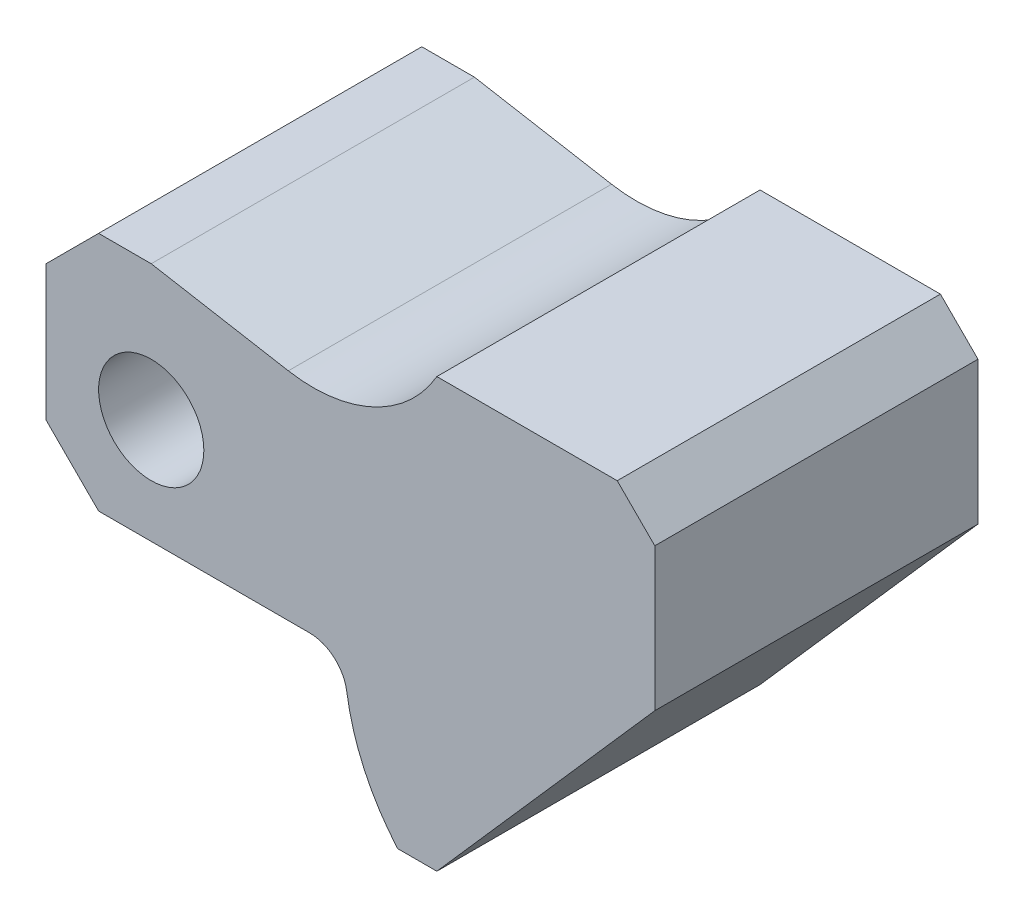
SolidWorks part; units mm, degrees
material "Brass"
ref_plane "Front Plane" through (0, 0, 0) normal (0, 0, 1) x (1, 0, 0)
ref_plane "Top Plane" through (0, 0, 0) normal (0, 1, 0) x (1, 0, 0)
ref_plane "Right Plane" through (0, 0, 0) normal (1, 0, 0) x (0, 0, -1)
sketch "Sketch1" plane through (0, 0, 0) normal (0, 0, 1) x (1, 0, 0)
  line L0 (-14, -7) -> (-14, 11)
  line L1 (-14, 11) -> (-7, 18)
  line L2 (-7, 18) -> (0, 18)
  line L3 (0, 18) -> (18.2431, 14.7833)
  line L4 (38, 24) -> (62, 24)
  line L5 (62, 24) -> (67, 19)
  line L6 (67, 19) -> (67, 0)
  line L7 (67, 0) -> (38, -33)
  line L8 (38, -33) -> (32.7881, -33)
  line L9 (-14, -7) -> (-7, -14)
  line L10 (-7, -14) -> (21.0666, -14)
  circle A0 centre (0, 0) radius 7
  arc A1 (18.2431, 14.7833) -> (38, 24) centre (21.5424, 33.4946) ccw
  arc A2 (21.0666, -14) -> (26.0123, -18.2647) centre (21.0666, -19) cw
  arc A3 (26.0123, -18.2647) -> (32.7881, -33) centre (54.697, -14) ccw
  dimension "D2" = 14
  dimension "D8" = 5
  dimension "D9" = 29
  dimension "D17" = 19
  dimension "D1" = 32
  dimension "D3" = 14
  dimension "D4" = 7
  dimension "D5" = 14
  dimension "D6" = 45
  dimension "D7" = 29
  dimension "D10" = 81
  dimension "D11" = 57
  dimension "D12" = 10
  dimension "D13" = 19
  dimension "D14" = 14
  dimension "D15" = 45
  dimension "D16" = 7
  dimension "D18" = 5
  dimension "D19" = 24
  dimension "D20" = 19
  dimension "D21" = 29
extrude "Boss-Extrude1" add sketch "Sketch1" along normal blind 43
equation "\"A\"=81"
equation "\"D10@Sketch1\"=\"A\""
equation "\"B\"=57"
equation "\"D11@Sketch1\"=\"B\""
equation "\"C\"=43"
equation "\"D1@Boss-Extrude1\"=\"C\""
